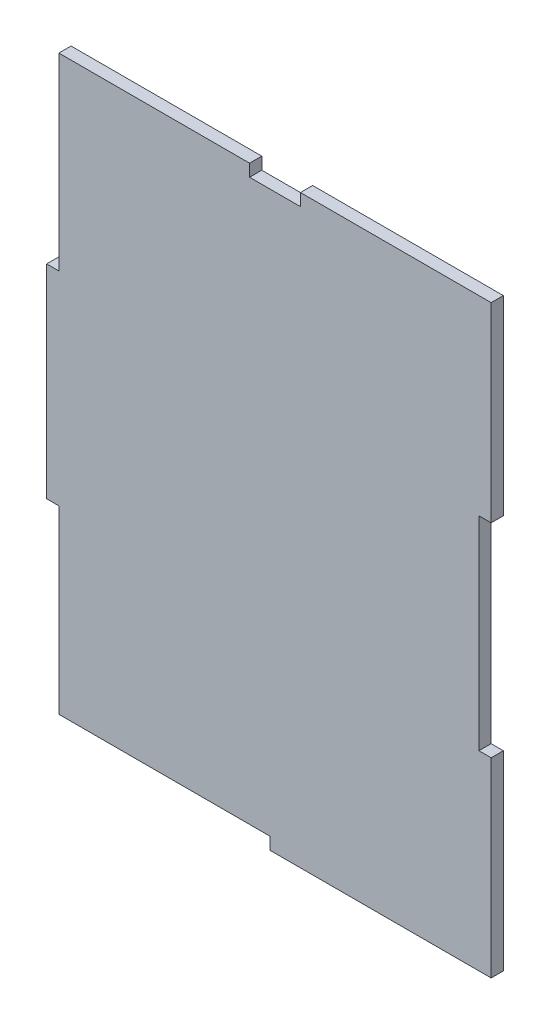
SolidWorks part; units mm, degrees
ref_plane "Přední rovina" through (0, 0, 0) normal (0, 0, 1) x (1, 0, 0)
ref_plane "Horní rovina" through (0, 0, 0) normal (0, 1, 0) x (1, 0, 0)
ref_plane "Pravá rovina" through (0, 0, 0) normal (1, 0, 0) x (0, 0, -1)
sketch "Skica1" plane through (0, 0, 0) normal (0, 0, 1) x (1, 0, 0)
  line L0 (1.6834, 36.2914) -> (1.6834, 0.7914)
  line L1 (1.6834, 113.3914) -> (39.1834, 113.3914)
  line L2 (1.6834, 113.3914) -> (1.6834, 76.2914)
  line L3 (43.1834, -1.6086) -> (86.6834, -1.6086)
  line L4 (86.6834, 113.3914) -> (86.6834, 75.8914)
  line L5 (39.1834, 113.3914) -> (39.1834, 110.9914)
  line L6 (39.1834, 110.9914) -> (49.1834, 110.9914)
  line L7 (49.1834, 113.3914) -> (49.1834, 110.9914)
  line L8 (1.6834, 0.7914) -> (43.1834, 0.7914)
  line L9 (43.1834, 0.7914) -> (43.1834, -1.6086)
  line L10 (1.6834, 76.2914) -> (-0.7166, 76.2914)
  line L11 (86.6834, 35.8914) -> (86.6834, -1.6086)
  line L12 (1.6834, 36.2914) -> (-0.7166, 36.2914)
  line L13 (-0.7166, 76.2914) -> (-0.7166, 36.2914)
  line L14 (86.6834, 75.8914) -> (84.2834, 75.8914)
  line L15 (49.1834, 113.3914) -> (86.6834, 113.3914)
  line L16 (86.6834, 35.8914) -> (84.2834, 35.8914)
  line L17 (84.2834, 75.8914) -> (84.2834, 35.8914)
  dimension "D1" = 85
  dimension "D2" = 2.4
  dimension "D3" = 2.4
  dimension "D4" = 40
  dimension "D5" = 115
  dimension "D6" = 10
  dimension "D7" = 37.5
extrude "Přidat vysunutím1" add sketch "Skica1" along normal blind 2.4
